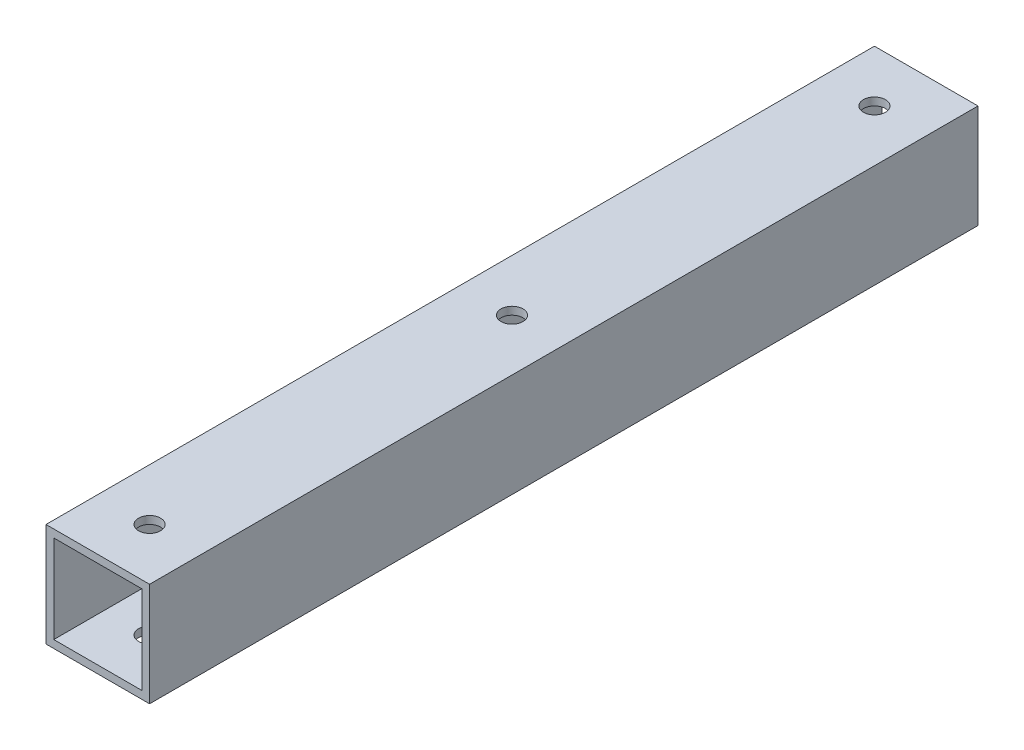
SolidWorks part; units mm, degrees
ref_plane "Front Plane" through (0, 0, 0) normal (0, 0, 1) x (1, 0, 0)
ref_plane "Top Plane" through (0, 0, 0) normal (0, 1, 0) x (1, 0, 0)
ref_plane "Right Plane" through (0, 0, 0) normal (1, 0, 0) x (0, 0, -1)
sketch "Sketch1" plane through (0, 0, 0) normal (0, 0, 1) x (1, 0, 0)
  line L0 (-8.5, -8.5) -> (8.5, -8.5)
  line L1 (-10, -10) -> (10, -10)
  line L2 (-10, -10) -> (-10, 10)
  line L3 (-10, 10) -> (10, 10)
  line L4 (10, -10) -> (10, 10)
  line L5 (-10, -10) -> (10, 10) construction
  line L6 (-10, 10) -> (10, -10) construction
  line L7 (8.5, -8.5) -> (8.5, 8.5)
  line L8 (-8.5, 8.5) -> (8.5, 8.5)
  line L9 (-8.5, -8.5) -> (-8.5, 8.5)
  point P0 (0, 0)
  dimension "D1" = 20
  dimension "D3" = 20
  dimension "D2" = 1.5
extrude "Boss-Extrude1" add sketch "Sketch1" against normal blind 160
sketch "Sketch2" plane through (0, 10, 0) normal (0, 1, 0) x (1, 0, 0)
  line L0 (10, 0) -> (-10, 0) construction
  circle A0 centre (0, 10) radius 2.125
  circle A6 centre (0, 80) radius 2.125
  circle A7 centre (0, 150) radius 2.125
  dimension "D1" = 4.25
  dimension "D2" = 10
extrude "Cut-Extrude1" cut sketch "Sketch2" against normal through all
